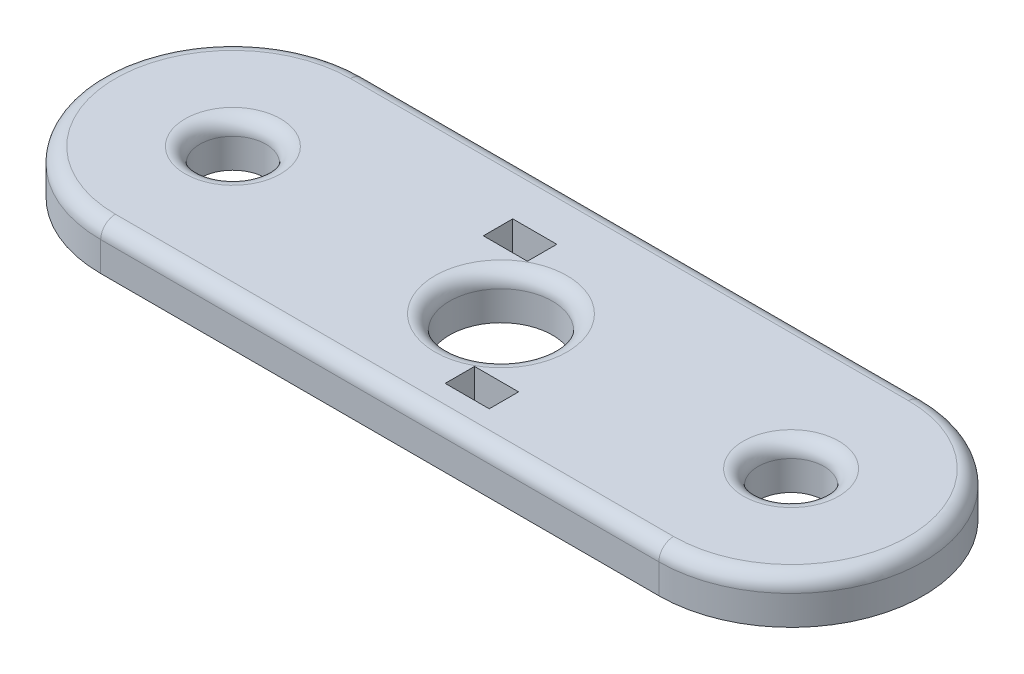
SolidWorks part; units mm, degrees
ref_plane "Front Plane" through (0, 0, 0) normal (0, 0, 1) x (1, 0, 0)
ref_plane "Top Plane" through (0, 0, 0) normal (0, 1, 0) x (1, 0, 0)
ref_plane "Right Plane" through (0, 0, 0) normal (1, 0, 0) x (0, 0, -1)
sketch "Sketch1" plane through (0, 0, 0) normal (0, 1, 0) x (1, 0, 0)
  line L1 (19, 9) -> (-19, 9)
  line L2 (19, 9) -> (19, -9) construction
  line L3 (19, -9) -> (-19, -9)
  line L4 (-19, 9) -> (-19, -9) construction
  line L5 (19, 9) -> (-19, -9) construction
  line L6 (19, -9) -> (-19, 9) construction
  arc A0 (-19, 9) -> (-19, -9) centre (-19, 0) ccw
  arc A1 (19, -9) -> (19, 9) centre (19, 0) ccw
  circle A2 centre (-19, 0) radius 2.25
  circle A3 centre (19, 0) radius 2.25
  circle A4 centre (0, -0.75) radius 3.5
  point P0 (0, 0)
  dimension "D2" = 4.5
  dimension "D5" = 7
  dimension "D1" = 18
  dimension "D3" = 38
  dimension "D4" = 0.75
extrude "Boss-Extrude1" add sketch "Sketch1" along normal blind 3
sketch "Sketch2" plane through (0, 0, 0) normal (0, -1, 0) x (1, 0, 0)
  line L0 (2.2, 6.75) -> (2.2, 4.75)
  line L7 (2.2, 4.75) -> (5.2, 4.75)
  line L8 (-5.2, -3.25) -> (-2.2, -3.25)
  line L9 (-2.2, -3.25) -> (-2.2, -5.25)
  line L10 (-5.2, -3.25) -> (-5.2, -5.25)
  line L11 (-5.2, -5.25) -> (-2.2, -5.25)
  line L12 (2.2, 6.75) -> (5.2, 6.75)
  line L13 (5.2, 6.75) -> (5.2, 4.75)
  dimension "D3" = 2
  dimension "D4" = 3
  dimension "D5" = 3
  dimension "D6" = 2
extrude "Cut-Extrude1" cut sketch "Sketch2" against normal through all both and the other way through all
fillet "Fillet1" radius 1 7 edges at (0, 3, -9) (28, 3, 0) (0, 3, 9) (19, 3, 2.25) (0, 3, 4.25) (-19, 3, 2.25) (-28, 3, 0)
